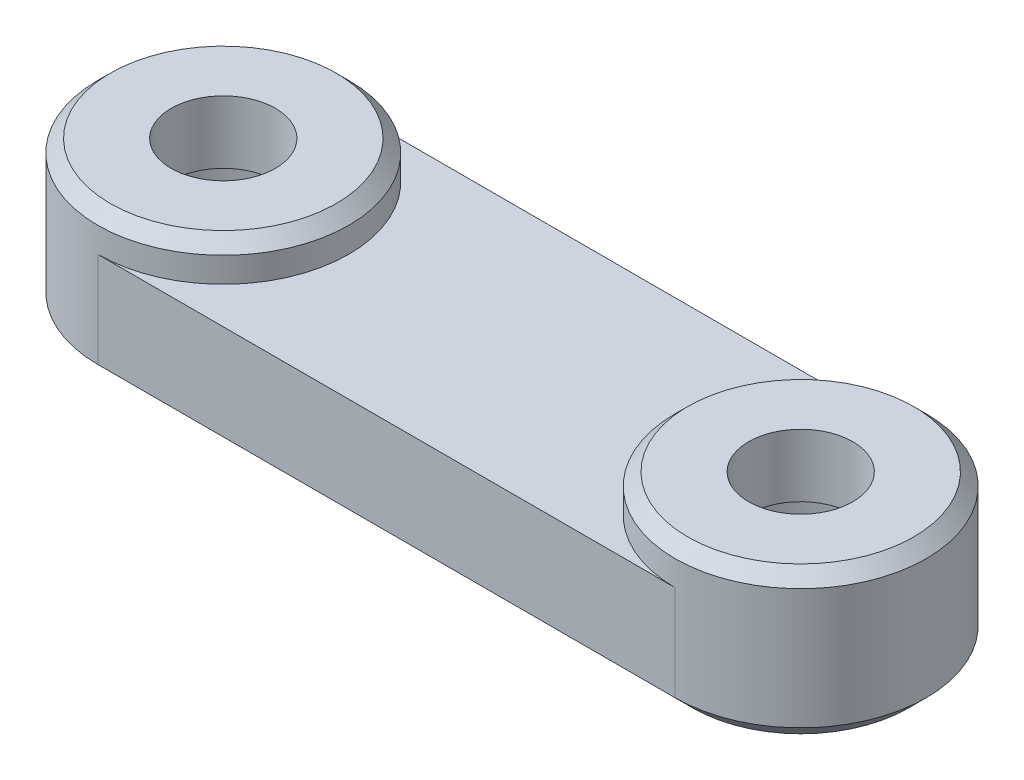
SolidWorks part; units mm, degrees
ref_plane "前视基准面" through (0, 0, 0) normal (0, 0, 1) x (1, 0, 0)
ref_plane "上视基准面" through (0, 0, 0) normal (0, 1, 0) x (1, 0, 0)
ref_plane "右视基准面" through (0, 0, 0) normal (1, 0, 0) x (0, 0, -1)
sketch "草图1" plane through (0, 0, 0) normal (0, 1, 0) x (1, 0, 0)
  line L0 (0, 0) -> (23, 0) construction
  line L1 (0, 5) -> (23, 5)
  line L2 (0, -5) -> (23, -5)
  arc A0 (0, 5) -> (0, -5) centre (0, 0) ccw
  arc A1 (23, -5) -> (23, 5) centre (23, 0) ccw
  point P3 (11.5, 0)
  dimension "D1" = 23
  dimension "D2" = 10
extrude "凸台-拉伸1" add sketch "草图1" along normal blind 6
sketch "草图2" plane through (0, 0, 0) normal (0, 0, 1) x (1, 0, 0)
  line L0 (0, 0) -> (0, 11.3662) construction
  line L1 (-3.75, 0) -> (-3.75, 3.5)
  line L2 (-5, 0) -> (0, 0) construction
  line L3 (-3.75, 3.5) -> (-2.075, 3.5)
  line L4 (-2.075, 3.5) -> (-2.075, 6)
  line L5 (0, 6) -> (-5, 6) construction
  line L6 (-2.075, 6) -> (0, 6)
  line L7 (-3.75, 0) -> (0, 0)
  line L8 (0, 0) -> (0, 6)
  dimension "D1" = 7.5
  dimension "D2" = 3.5
  dimension "D3" = 4.15
revolve "切除-旋转1" cut sketch "草图2" angle 360 about L0
sketch "草图3" plane through (0, 0, 0) normal (0, 0, 1) x (1, 0, 0)
  line L0 (23, 0) -> (23, 9.724) construction
  line L1 (23, 0) -> (19.25, 0)
  line L2 (0, 0) -> (23, 0) construction
  line L3 (19.25, 0) -> (19.25, 3.5)
  line L4 (19.25, 3.5) -> (20.925, 3.5)
  line L5 (20.925, 3.5) -> (20.925, 6)
  line L6 (0, 6) -> (23, 6) construction
  line L7 (20.925, 6) -> (23, 6)
  line L8 (23, 0) -> (23, 6)
  dimension "D1" = 7.5
  dimension "D2" = 3.5
  dimension "D3" = 4.15
revolve "切除-旋转2" cut sketch "草图3" angle 360 about L0
sketch "草图4" plane through (0, 6, 0) normal (0, 1, 0) x (1, 0, 0)
  line L1 (52.0748, 24.9894) -> (-22.7163, 24.9894)
  line L2 (52.0748, 24.9894) -> (52.0748, -22.1578)
  line L3 (52.0748, -22.1578) -> (-22.7163, -22.1578)
  line L4 (-22.7163, 24.9894) -> (-22.7163, -22.1578)
  circle A0 centre (23, 0) radius 5
  circle A1 centre (0, 0) radius 5
  point P13 (-7.6651, -2.93)
  point P16 (0, 0)
  dimension "D1" = 10
  dimension "D2" = 10
extrude "切除-拉伸1" cut sketch "草图4" against normal blind 1.5
chamfer "倒角1" distance 0.5 angle 45 2 edges at (0, 6, 5) (23, 6, 5)
chamfer "倒角2" distance 0.7 angle 45 4 edges at (11.5, 0, -5) (-5, 0, 0) (28, 0, 0) (11.5, 0, 5)
